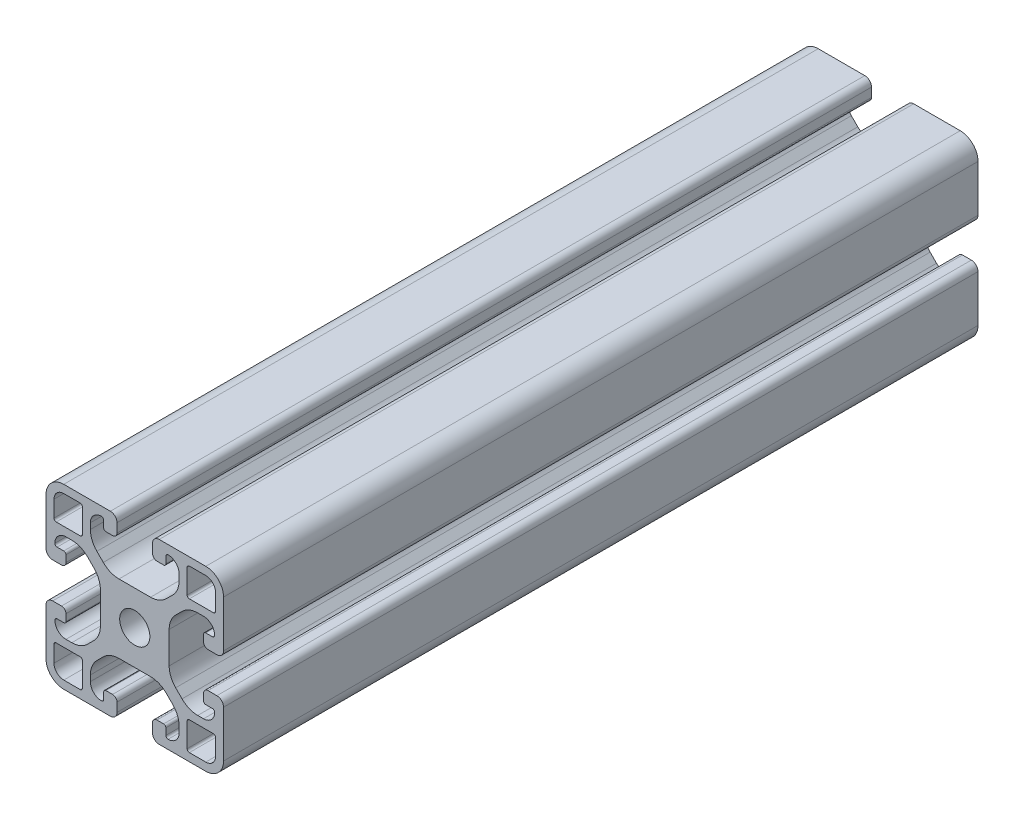
SolidWorks part; units mm, degrees
ref_plane "Plan de face" through (0, 0, 0) normal (0, 0, 1) x (1, 0, 0)
ref_plane "Plan de dessus" through (0, 0, 0) normal (0, 1, 0) x (1, 0, 0)
ref_plane "Plan de droite" through (0, 0, 0) normal (1, 0, 0) x (0, 0, -1)
ref_plane "Plan1" through (0, 0, -30) normal (0, 0, -1) x (-1, 0, 0)
sketch "Esquisse1" plane through (0, 0, -30) normal (0, 0, -1) x (-1, 0, 0)
  line L0 (-4.5, 15) -> (-4.5, 13.5)
  line L1 (-4, 13) -> (-2.5, 13)
  line L2 (-4.5, 10) -> (-5.8076, 10)
  line L3 (-9.3431, 11.4645) -> (-10.7855, 12.9069)
  line L4 (-12.25, 16.4424) -> (-12.25, 23.5576)
  line L5 (-10.7855, 27.0931) -> (-9.3431, 28.5355)
  line L6 (-5.8076, 30) -> (-4.5, 30)
  line L7 (-2.5, 27) -> (-4, 27)
  line L8 (-4.5, 26.5) -> (-4.5, 25)
  line L9 (-3.5, 24) -> (-1.5, 24)
  line L10 (0, 25.5) -> (0, 36)
  line L11 (-4, 40) -> (-14.5, 40)
  line L12 (-16, 38.5) -> (-16, 36.5)
  line L13 (-15, 35.5) -> (-13.5, 35.5)
  line L14 (-13, 36) -> (-13, 37.5)
  line L15 (-10, 35.5) -> (-10, 34.1924)
  line L16 (-11.4645, 30.6569) -> (-12.9069, 29.2145)
  line L17 (-16.4424, 27.75) -> (-23.5576, 27.75)
  line L18 (-27.0931, 29.2145) -> (-28.5355, 30.6569)
  line L19 (-30, 34.1924) -> (-30, 35.5)
  line L20 (-27, 37.5) -> (-27, 36)
  line L21 (-26.5, 35.5) -> (-25, 35.5)
  line L22 (-24, 36.5) -> (-24, 38.5)
  line L23 (-25.5, 40) -> (-36, 40)
  line L24 (-40, 36) -> (-40, 25.5)
  line L25 (-38.5, 24) -> (-36.5, 24)
  line L26 (-35.5, 25) -> (-35.5, 26.5)
  line L27 (-36, 27) -> (-37.5, 27)
  line L28 (-35.5, 30) -> (-34.1924, 30)
  line L29 (-30.6569, 28.5355) -> (-29.2145, 27.0931)
  line L30 (-27.75, 23.5576) -> (-27.75, 16.4424)
  line L31 (-29.2145, 12.9069) -> (-30.6569, 11.4645)
  line L32 (-34.1924, 10) -> (-35.5, 10)
  line L33 (-37.5, 13) -> (-36, 13)
  line L34 (-35.5, 13.5) -> (-35.5, 15)
  line L35 (-36.5, 16) -> (-38.5, 16)
  line L36 (-40, 14.5) -> (-40, 4)
  line L37 (-36, 0) -> (-25.5, 0)
  line L38 (-24, 1.5) -> (-24, 3.5)
  line L39 (-25, 4.5) -> (-26.5, 4.5)
  line L40 (-27, 4) -> (-27, 2.5)
  line L41 (-30, 4.5) -> (-30, 5.8076)
  line L42 (-28.5355, 9.3431) -> (-27.0931, 10.7855)
  line L43 (-23.5576, 12.25) -> (-16.4424, 12.25)
  line L44 (-12.9069, 10.7855) -> (-11.4645, 9.3431)
  line L45 (-10, 5.8076) -> (-10, 4.5)
  line L46 (-13, 2.5) -> (-13, 4)
  line L47 (-13.5, 4.5) -> (-15, 4.5)
  line L48 (-16, 3.5) -> (-16, 1.5)
  line L49 (-14.5, 0) -> (-4, 0)
  line L50 (0, 4) -> (0, 14.5)
  line L51 (-1.5, 16) -> (-3.5, 16)
  line L52 (-4, 1.8) -> (-7.7, 1.8)
  line L53 (-8.2, 2.3) -> (-8.2, 7.7)
  line L54 (-7.7, 8.2) -> (-2.3, 8.2)
  line L55 (-1.8, 7.7) -> (-1.8, 4)
  line L56 (-38.2, 4) -> (-38.2, 7.7)
  line L57 (-37.7, 8.2) -> (-32.3, 8.2)
  line L58 (-31.8, 7.7) -> (-31.8, 2.3)
  line L59 (-32.3, 1.8) -> (-36, 1.8)
  line L60 (-36, 38.2) -> (-32.3, 38.2)
  line L61 (-31.8, 37.7) -> (-31.8, 32.3)
  line L62 (-32.3, 31.8) -> (-37.7, 31.8)
  line L63 (-38.2, 32.3) -> (-38.2, 36)
  line L64 (-1.8, 36) -> (-1.8, 32.3)
  line L65 (-2.3, 31.8) -> (-7.7, 31.8)
  line L66 (-8.2, 32.3) -> (-8.2, 37.7)
  line L67 (-7.7, 38.2) -> (-4, 38.2)
  arc A0 (-4.5, 13.5) -> (-4, 13) centre (-4, 13.5) ccw
  arc A1 (-2.5, 13) -> (-2, 12.5) centre (-2.5, 12.5) cw
  arc A2 (-2, 12.5) -> (-4.5, 10) centre (-4.5, 12.5) cw
  arc A3 (-5.8076, 10) -> (-9.3431, 11.4645) centre (-5.8076, 15) cw
  arc A4 (-10.7855, 12.9069) -> (-12.25, 16.4424) centre (-7.25, 16.4424) cw
  arc A5 (-12.25, 23.5576) -> (-10.7855, 27.0931) centre (-7.25, 23.5576) cw
  arc A6 (-9.3431, 28.5355) -> (-5.8076, 30) centre (-5.8076, 25) cw
  arc A7 (-4.5, 30) -> (-2, 27.5) centre (-4.5, 27.5) cw
  arc A8 (-2, 27.5) -> (-2.5, 27) centre (-2.5, 27.5) cw
  arc A9 (-4, 27) -> (-4.5, 26.5) centre (-4, 26.5) ccw
  arc A10 (-4.5, 25) -> (-3.5, 24) centre (-3.5, 25) ccw
  arc A11 (-1.5, 24) -> (0, 25.5) centre (-1.5, 25.5) ccw
  arc A12 (0, 36) -> (-4, 40) centre (-4, 36) ccw
  arc A13 (-14.5, 40) -> (-16, 38.5) centre (-14.5, 38.5) ccw
  arc A14 (-16, 36.5) -> (-15, 35.5) centre (-15, 36.5) ccw
  arc A15 (-13.5, 35.5) -> (-13, 36) centre (-13.5, 36) ccw
  arc A16 (-13, 37.5) -> (-12.5, 38) centre (-12.5, 37.5) cw
  arc A17 (-12.5, 38) -> (-10, 35.5) centre (-12.5, 35.5) cw
  arc A18 (-10, 34.1924) -> (-11.4645, 30.6569) centre (-15, 34.1924) cw
  arc A19 (-12.9069, 29.2145) -> (-16.4424, 27.75) centre (-16.4424, 32.75) cw
  arc A20 (-23.5576, 27.75) -> (-27.0931, 29.2145) centre (-23.5576, 32.75) cw
  arc A21 (-28.5355, 30.6569) -> (-30, 34.1924) centre (-25, 34.1924) cw
  arc A22 (-30, 35.5) -> (-27.5, 38) centre (-27.5, 35.5) cw
  arc A23 (-27.5, 38) -> (-27, 37.5) centre (-27.5, 37.5) cw
  arc A24 (-27, 36) -> (-26.5, 35.5) centre (-26.5, 36) ccw
  arc A25 (-25, 35.5) -> (-24, 36.5) centre (-25, 36.5) ccw
  arc A26 (-24, 38.5) -> (-25.5, 40) centre (-25.5, 38.5) ccw
  arc A27 (-36, 40) -> (-40, 36) centre (-36, 36) ccw
  arc A28 (-40, 25.5) -> (-38.5, 24) centre (-38.5, 25.5) ccw
  arc A29 (-36.5, 24) -> (-35.5, 25) centre (-36.5, 25) ccw
  arc A30 (-35.5, 26.5) -> (-36, 27) centre (-36, 26.5) ccw
  arc A31 (-37.5, 27) -> (-38, 27.5) centre (-37.5, 27.5) cw
  arc A32 (-38, 27.5) -> (-35.5, 30) centre (-35.5, 27.5) cw
  arc A33 (-34.1924, 30) -> (-30.6569, 28.5355) centre (-34.1924, 25) cw
  arc A34 (-29.2145, 27.0931) -> (-27.75, 23.5576) centre (-32.75, 23.5576) cw
  arc A35 (-27.75, 16.4424) -> (-29.2145, 12.9069) centre (-32.75, 16.4424) cw
  arc A36 (-30.6569, 11.4645) -> (-34.1924, 10) centre (-34.1924, 15) cw
  arc A37 (-35.5, 10) -> (-38, 12.5) centre (-35.5, 12.5) cw
  arc A38 (-38, 12.5) -> (-37.5, 13) centre (-37.5, 12.5) cw
  arc A39 (-36, 13) -> (-35.5, 13.5) centre (-36, 13.5) ccw
  arc A40 (-35.5, 15) -> (-36.5, 16) centre (-36.5, 15) ccw
  arc A41 (-38.5, 16) -> (-40, 14.5) centre (-38.5, 14.5) ccw
  arc A42 (-40, 4) -> (-36, 0) centre (-36, 4) ccw
  arc A43 (-25.5, 0) -> (-24, 1.5) centre (-25.5, 1.5) ccw
  arc A44 (-24, 3.5) -> (-25, 4.5) centre (-25, 3.5) ccw
  arc A45 (-26.5, 4.5) -> (-27, 4) centre (-26.5, 4) ccw
  arc A46 (-27, 2.5) -> (-27.5, 2) centre (-27.5, 2.5) cw
  arc A47 (-27.5, 2) -> (-30, 4.5) centre (-27.5, 4.5) cw
  arc A48 (-30, 5.8076) -> (-28.5355, 9.3431) centre (-25, 5.8076) cw
  arc A49 (-27.0931, 10.7855) -> (-23.5576, 12.25) centre (-23.5576, 7.25) cw
  arc A50 (-16.4424, 12.25) -> (-12.9069, 10.7855) centre (-16.4424, 7.25) cw
  arc A51 (-11.4645, 9.3431) -> (-10, 5.8076) centre (-15, 5.8076) cw
  arc A52 (-10, 4.5) -> (-12.5, 2) centre (-12.5, 4.5) cw
  arc A53 (-12.5, 2) -> (-13, 2.5) centre (-12.5, 2.5) cw
  arc A54 (-13, 4) -> (-13.5, 4.5) centre (-13.5, 4) ccw
  arc A55 (-15, 4.5) -> (-16, 3.5) centre (-15, 3.5) ccw
  arc A56 (-16, 1.5) -> (-14.5, 0) centre (-14.5, 1.5) ccw
  arc A57 (-4, 0) -> (0, 4) centre (-4, 4) ccw
  arc A58 (0, 14.5) -> (-1.5, 16) centre (-1.5, 14.5) ccw
  arc A59 (-3.5, 16) -> (-4.5, 15) centre (-3.5, 15) ccw
  circle A60 centre (-20, 20) radius 3.4
  arc A61 (-1.8, 4) -> (-4, 1.8) centre (-4, 4) cw
  arc A62 (-7.7, 1.8) -> (-8.2, 2.3) centre (-7.7, 2.3) cw
  arc A63 (-8.2, 7.7) -> (-7.7, 8.2) centre (-7.7, 7.7) cw
  arc A64 (-2.3, 8.2) -> (-1.8, 7.7) centre (-2.3, 7.7) cw
  arc A65 (-36, 1.8) -> (-38.2, 4) centre (-36, 4) cw
  arc A66 (-38.2, 7.7) -> (-37.7, 8.2) centre (-37.7, 7.7) cw
  arc A67 (-32.3, 8.2) -> (-31.8, 7.7) centre (-32.3, 7.7) cw
  arc A68 (-31.8, 2.3) -> (-32.3, 1.8) centre (-32.3, 2.3) cw
  arc A69 (-38.2, 36) -> (-36, 38.2) centre (-36, 36) cw
  arc A70 (-32.3, 38.2) -> (-31.8, 37.7) centre (-32.3, 37.7) cw
  arc A71 (-31.8, 32.3) -> (-32.3, 31.8) centre (-32.3, 32.3) cw
  arc A72 (-37.7, 31.8) -> (-38.2, 32.3) centre (-37.7, 32.3) cw
  arc A73 (-4, 38.2) -> (-1.8, 36) centre (-4, 36) cw
  arc A74 (-1.8, 32.3) -> (-2.3, 31.8) centre (-2.3, 32.3) cw
  arc A75 (-7.7, 31.8) -> (-8.2, 32.3) centre (-7.7, 32.3) cw
  arc A76 (-8.2, 37.7) -> (-7.7, 38.2) centre (-7.7, 37.7) cw
extrude "Boss.-Extru.1" add sketch "Esquisse1" against normal blind 170
